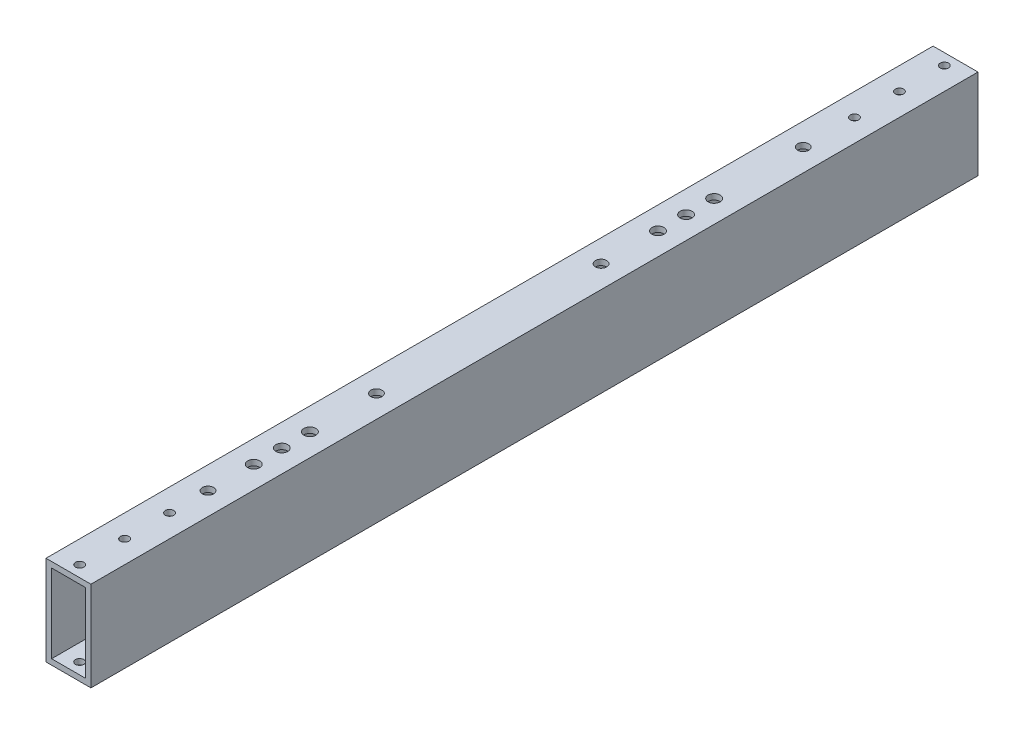
SolidWorks part; units mm, degrees
material "6061-T6 (SS)"
ref_plane "Front Plane" through (0, 0, 0) normal (0, 0, 1) x (1, 0, 0)
ref_plane "Top Plane" through (0, 0, 0) normal (0, 1, 0) x (1, 0, 0)
ref_plane "Right Plane" through (0, 0, 0) normal (1, 0, 0) x (0, 0, -1)
sketch "Sketch1" plane through (0, 0, 0) normal (0, 0, 1) x (1, 0, 0)
  line L1 (-12.7, -25.4) -> (12.7, -25.4)
  line L2 (-12.7, -25.4) -> (-12.7, 25.4)
  line L3 (-12.7, 25.4) -> (12.7, 25.4)
  line L4 (12.7, -25.4) -> (12.7, 25.4)
  line L5 (-12.7, -25.4) -> (12.7, 25.4) construction
  line L6 (-12.7, 25.4) -> (12.7, -25.4) construction
  point P0 (0, 0)
  dimension "D1" = 50.8
  dimension "D2" = 25.4
extrude "Extrude-Thin1" add sketch "Sketch1" along normal blind 501.65 thin thin type one direction reverse wall 3.175
hole_wizard "3/16 (0.1875) Diameter Hole1" positions "3DSketch1" profile "Sketch3" hole size "3/16" standard "ANSI Inch" end condition through all
sketch3d "3DSketch1"
  line L1 (12.7, 25.4, 0) -> (-12.7, 25.4, 0) construction
  line L6 (0, 25.4, 501.65) -> (0, 25.4, 0) construction
  line L7 (12.7, 25.4, 501.65) -> (-12.7, 25.4, 501.65) construction
  point P57 (0, 25.4, 6.35)
  point P59 (0, 25.4, 31.75)
  point P61 (0, 25.4, 57.15)
  point P63 (0, 25.4, 469.9)
  point P65 (0, 25.4, 444.5)
  point P67 (0, 25.4, 495.3)
  dimension "D1" = 25.4
  dimension "D2" = 25.4
  dimension "D3" = 6.35
  dimension "D4" = 25.4
  dimension "D5" = 25.4
  dimension "D6" = 6.35
sketch "Sketch3" plane through (0, 25.4, 495.3) normal (1, 0, 0) x (0, 0, 1)
  line L0 (0, 0) -> (0, 50.8)
  line L1 (0, 50.8) -> (2.3812, 50.8)
  line L2 (2.3812, 50.8) -> (2.3812, 0)
  line L5 (2.3812, 0) -> (0, 0)
  line L11 (0, -6.35) -> (0, 107.95) construction
  dimension "Thru Hole Dia." = 4.7625
  dimension "Thru Hole Depth" = 50.8
hole_wizard "3/16 (0.195) Diameter Hole1" positions "Sketch4" profile "Sketch5" hole size "3/16" standard "ANSI Inch"
sketch "Sketch4" plane through (0, -25.4, 0) normal (0, -1, 0) x (-1, 0, 0)
  point P74 (-3.175, -85.7193)
  point P78 (3.175, -111.1193)
  point P81 (-3.175, -136.5193)
  point P84 (3.175, -161.9193)
  point P87 (-3.175, -187.3193)
  point P90 (3.175, -212.7193)
  point P93 (-3.175, -238.1193)
  point P96 (3.175, -263.5193)
  point P99 (-3.175, -288.9193)
  point P102 (3.175, -314.3193)
  point P105 (-3.175, -339.7193)
  point P108 (3.175, -365.1193)
  point P111 (3.175, -415.9193)
  point P114 (-3.175, -390.5193)
sketch "Sketch5" plane through (3.175, -25.4, 85.7193) normal (1, 0, 0) x (0, 0, -1)
  line L0 (0, 0) -> (0, 3.175)
  line L1 (0, 3.175) -> (2.4765, 3.175)
  line L2 (2.4765, 3.175) -> (2.4765, 0)
  line L5 (2.4765, 0) -> (0, 0)
  line L11 (0, -6.35) -> (0, 107.95) construction
  dimension "Thru Hole Dia." = 4.953
  dimension "Thru Hole Depth" = 3.175
hole_wizard "1/4 (0.25) Diameter Hole1" positions "Sketch6" profile "Sketch7" hole size "1/4" standard "ANSI Inch"
sketch "Sketch6" plane through (0, 25.4, 0) normal (0, 1, 0) x (1, 0, 0)
  point P0 (0, -200.4645)
  point P15 (0, -422.731)
  point P23 (0, -327.481)
  point P26 (0, -86.1545)
sketch "Sketch7" plane through (0, 25.4, 200.4645) normal (1, 0, 0) x (0, 0, 1)
  line L0 (0, 0) -> (0, 27.3077)
  line L1 (0, 27.3077) -> (3.175, 25.4)
  line L2 (3.175, 25.4) -> (3.175, 0)
  line L5 (3.175, 0) -> (0, 0)
  line L10 (0, 27.3077) -> (-3.175, 25.4) construction
  line L11 (0, -6.35) -> (0, 107.95) construction
  dimension "Hole Dia." = 6.35
  dimension "Hole Depth" = 25.4
  dimension "Drill Angle" = 118
hole_wizard "1/4 Clearance Hole1" positions "Sketch17" profile "Sketch18" hole size "1/4" standard "ANSI Inch"
sketch "Sketch17" plane through (-381, 25.4, 250.825) normal (0, 1, 0) x (1, 0, 0)
  point P0 (381, 82.55)
  point P3 (381, 98.425)
  point P6 (381, 114.3)
  point P9 (381, -146.05)
  point P12 (381, -130.175)
  point P15 (381, -114.3)
  point P18 (-381, -146.05)
  point P21 (-381, -130.175)
  point P24 (-381, -114.3)
  point P27 (-381, 82.55)
  point P30 (-381, 98.425)
  point P33 (-381, 114.3)
sketch "Sketch18" plane through (0, 25.4, 168.275) normal (1, 0, 0) x (0, 0, 1)
  line L0 (0, 0) -> (0, 40.1298)
  line L1 (0, 40.1298) -> (3.3782, 38.1)
  line L2 (3.3782, 38.1) -> (3.3782, 0)
  line L3 (3.3782, 0) -> (0, 0)
  line L4 (0, 40.1298) -> (-3.3782, 38.1) construction
  line L5 (0, -6.35) -> (0, 107.95) construction
  dimension "Hole Dia." = 6.7564
  dimension "Hole Depth" = 38.1
  dimension "Drill Angle" = 118
